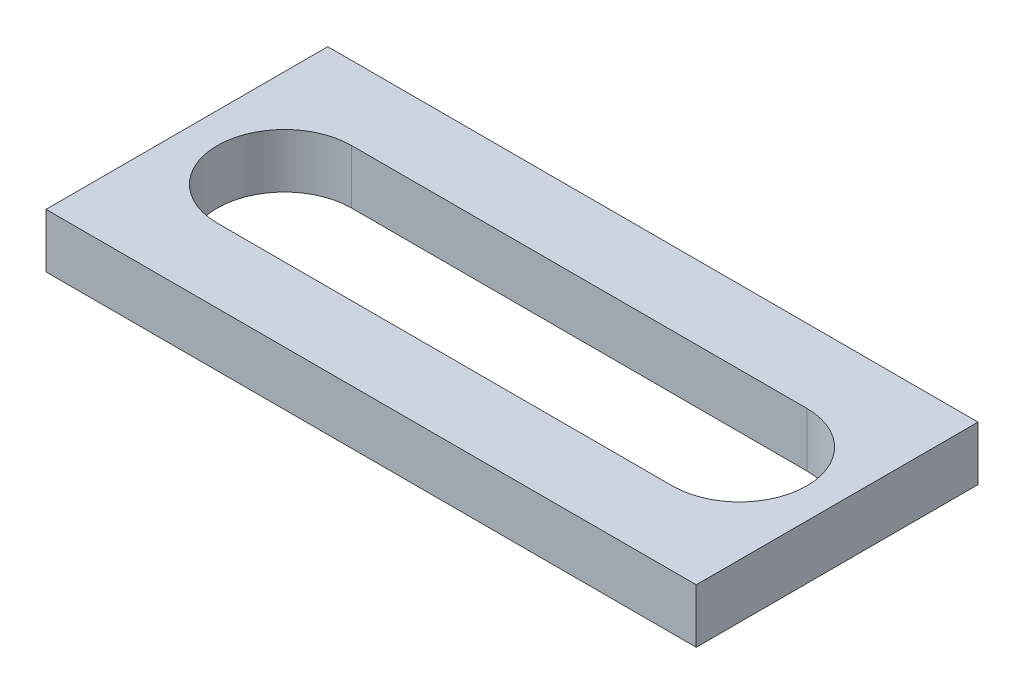
SolidWorks part; units mm, degrees
material "AISI 304"
ref_plane "前视基准面" through (0, 0, 0) normal (0, 0, 1) x (1, 0, 0)
ref_plane "上视基准面" through (0, 0, 0) normal (0, 1, 0) x (1, 0, 0)
ref_plane "右视基准面" through (0, 0, 0) normal (1, 0, 0) x (0, 0, -1)
sketch "Sketch1" plane through (0, 0, 0) normal (0, 1, 0) x (1, 0, 0)
  line L0 (-10.5, 0) -> (10.5, 0) construction
  line L1 (-15, 6.5) -> (15, 6.5)
  line L2 (-15, 6.5) -> (-15, -6.5)
  line L3 (-15, -6.5) -> (15, -6.5)
  line L4 (15, 6.5) -> (15, -6.5)
  line L5 (0, -6.5) -> (0, 6.5) construction
  line L6 (-15, 0) -> (15, 0) construction
  line L7 (-10.5, 3.1) -> (10.5, 3.1)
  line L8 (-10.5, -3.1) -> (10.5, -3.1)
  arc A0 (-10.5, 3.1) -> (-10.5, -3.1) centre (-10.5, 0) ccw
  arc A1 (10.5, -3.1) -> (10.5, 3.1) centre (10.5, 0) ccw
  point P0 (0, 0)
  point P6 (0, 0)
  point P11 (0, 0)
  dimension "D3" = 3.1
  dimension "D1" = 30
  dimension "D2" = 13
  dimension "D4" = 21
extrude "Boss-Extrude1" add sketch "Sketch1" along normal blind 2.5
